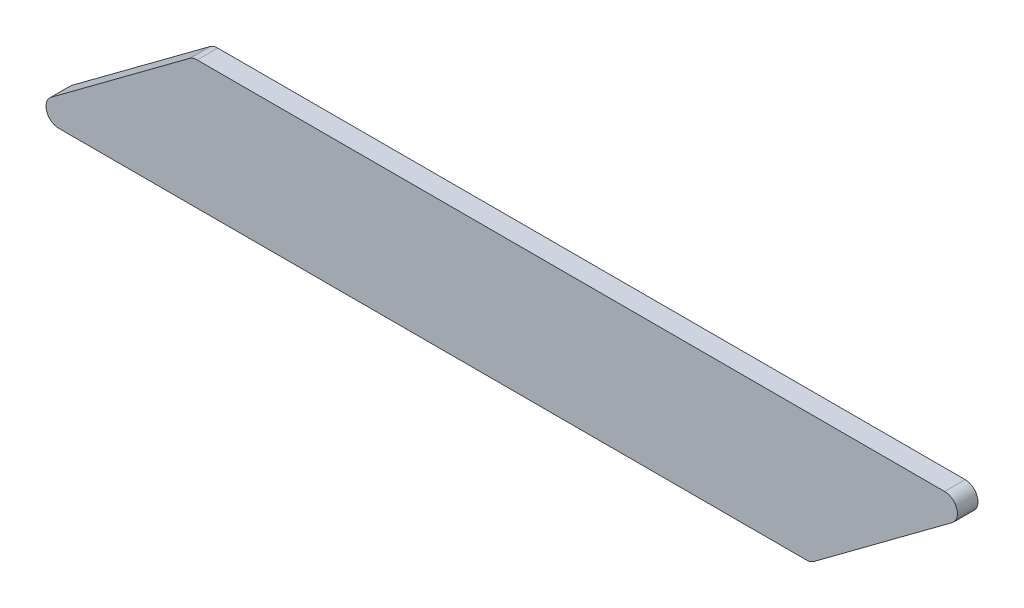
SolidWorks part; units mm, degrees
material "3003-H18"
ref_plane "X-Y Datum" through (0, 0, 0) normal (0, 0, 1) x (1, 0, 0)
ref_plane "X-Z Datum" through (0, 0, 0) normal (0, 1, 0) x (1, 0, 0)
ref_plane "Y-Z Datum" through (0, 0, 0) normal (1, 0, 0) x (0, 0, -1)
sketch "Sketch1" plane through (0, 0, 0) normal (0, 0, 1) x (1, 0, 0)
  line L1 (-37.5, -5) -> (37.5, -5)
  line L2 (-37.5, -5) -> (-37.5, 5)
  line L3 (-37.5, 5) -> (37.5, 5)
  line L4 (37.5, -5) -> (37.5, 5)
  line L5 (-37.5, -5) -> (37.5, 5) construction
  line L6 (-37.5, 5) -> (37.5, -5) construction
  point P0 (0, 0)
  dimension "D1" = 75
  dimension "D2" = 10
extrude "Boss-Extrude1" add sketch "Sketch1" along normal blind 1.6
sketch "Sketch2" plane through (0, 0, 1.6) normal (0, 0, 1) x (1, 0, 0)
  line L1 (-37.5, -5) -> (37.5, -5) construction
  line L2 (37.5, 5) -> (24.0455, -5)
  line L4 (37.5, 5) -> (-37.5, 5) construction
  line L5 (-37.5, -5) -> (-24.0455, 5)
extrude "Cut-Extrude1" cut sketch "Sketch2" against normal blind 10 and the other way through all
fillet "Fillet2" radius 1 4 edges at (24.0455, -5, 0.8) (37.5, 5, 0.8) (-24.0455, 5, 0.8) (-37.5, -5, 0.8)
